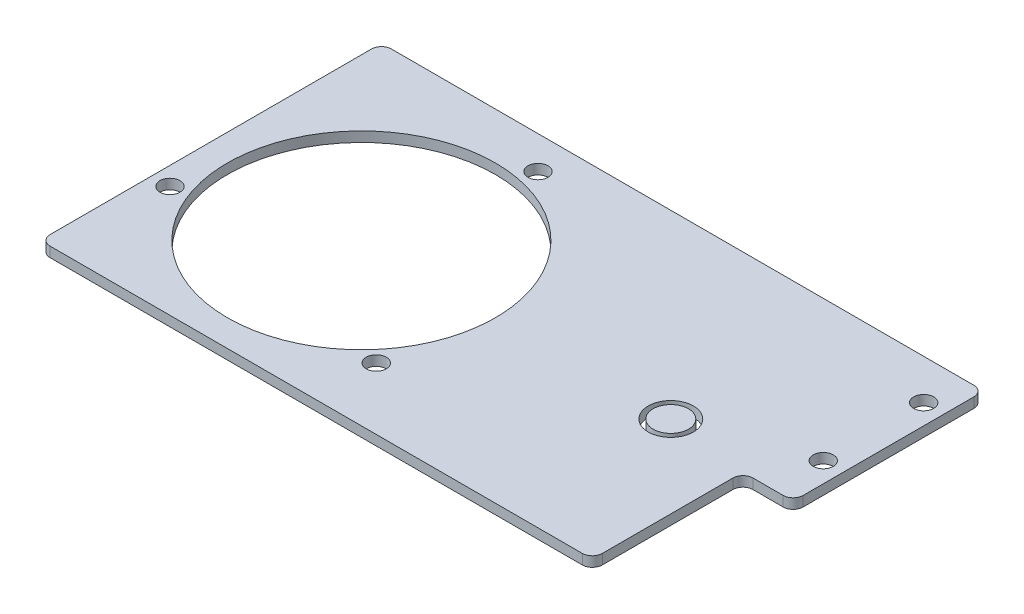
SolidWorks part; units mm, degrees
ref_plane "Front Plane" through (0, 0, 0) normal (0, 0, 1) x (1, 0, 0)
ref_plane "Top Plane" through (0, 0, 0) normal (0, 1, 0) x (1, 0, 0)
ref_plane "Right Plane" through (0, 0, 0) normal (1, 0, 0) x (0, 0, -1)
sketch "Sketch1" plane through (0, 0, 0) normal (0, 1, 0) x (1, 0, 0)
  line L0 (0, 114.3) -> (0, -101.6) construction
  line L1 (273.05, 114.3) -> (-95.25, 114.3)
  line L2 (279.4, 107.95) -> (279.4, 0)
  line L3 (241.3, -101.6) -> (-95.25, -101.6)
  line L4 (-101.6, 107.95) -> (-101.6, -95.25)
  line L5 (254, -6.35) -> (273.05, -6.35)
  line L6 (266.7, 0) -> (266.7, 114.3) construction
  line L7 (-101.6, 0) -> (285.75, 0) construction
  line L8 (0, 0) -> (-101.6, -34.9837) construction
  line L11 (247.65, -95.25) -> (247.65, -12.7)
  circle A0 centre (0, 0) radius 84.7725
  circle A1 centre (0, 0) radius 95.25 construction
  circle A2 centre (-90.0606, -31.0104) radius 6.35
  arc A3 (247.65, -12.7) -> (254, -6.35) centre (254, -12.7) cw
  arc A4 (-95.25, 114.3) -> (-101.6, 107.95) centre (-95.25, 107.95) ccw
  circle A5 centre (18.1746, 93.5) radius 6.35
  circle A6 centre (71.8861, -62.4896) radius 6.35
  arc A7 (-95.25, -101.6) -> (-101.6, -95.25) centre (-95.25, -95.25) cw
  arc A8 (241.3, -101.6) -> (247.65, -95.25) centre (241.3, -95.25) ccw
  arc A9 (273.05, -6.35) -> (279.4, 0) centre (273.05, 0) ccw
  arc A10 (273.05, 114.3) -> (279.4, 107.95) centre (273.05, 107.95) cw
  circle A11 centre (266.7, 88.9) radius 6.35
  circle A12 centre (266.7, 25.4) radius 6.35
  point P0 (0, 0)
  point P11 (0, 0)
  point P21 (247.65, -6.35)
  point P32 (247.65, -101.6)
  point P46 (0, 0)
  dimension "D3" = 169.545
  dimension "D5" = 190.5
  dimension "D6" = 12.7
  dimension "D7" = 114.3
  dimension "D8" = 279.4
  dimension "D11" = 6.35
  dimension "D14" = 12.7
  dimension "D1" = 101.6
  dimension "D2" = 101.6
  dimension "D4" = 19
  dimension "D9" = 95.25
  dimension "D10" = 31.75
  dimension "D13" = 12.7
  dimension "D15" = 25.4
extrude "Boss-Extrude1" add sketch "Sketch1" along normal blind 6.35
sketch "Sketch2" plane through (0, 0, 0) normal (0, -1, 0) x (1, 0, 0)
  line L0 (-101.6, -107.95) -> (-101.6, 95.25) construction
  line L1 (273.05, -114.3) -> (-95.25, -114.3) construction
  line L2 (279.4, 0) -> (279.4, -107.95) construction
  line L3 (-95.25, 101.6) -> (241.3, 101.6) construction
  line L4 (-101.6, -107.95) -> (-101.6, 95.25)
  line L5 (273.05, -114.3) -> (-95.25, -114.3)
  line L6 (279.4, 0) -> (279.4, -107.95)
  line L7 (-95.25, 101.6) -> (241.3, 101.6)
  line L8 (88.9, -114.3) -> (88.9, 101.6) construction
  line L9 (-101.6, -6.35) -> (279.4, -6.35) construction
  line L11 (333.375, 146.05) -> (-155.575, 146.05)
  line L12 (333.375, 146.05) -> (333.375, -158.75)
  line L13 (333.375, -158.75) -> (-155.575, -158.75)
  line L14 (-155.575, 146.05) -> (-155.575, -158.75)
  line L15 (333.375, 146.05) -> (-155.575, -158.75) construction
  line L16 (333.375, -158.75) -> (-155.575, 146.05) construction
  point P12 (88.9, -6.35)
  dimension "D1" = 381
  dimension "D2" = 215.9
  dimension "D3" = 488.95
  dimension "D4" = 304.8
sketch "Sketch3" plane through (0, 6.35, 0) normal (0, 1, 0) x (1, 0, 0)
  circle A0 centre (0, 0) radius 84.7725 construction
  point P0 (84.7725, 0)
sketch "Sketch4" plane through (0, 6.35, 0) normal (0, 1, 0) x (1, 0, 0)
  circle A1 centre (195.6867, 0) radius 11.176 construction
  circle A2 centre (195.6867, 0) radius 14.2875
  circle A3 centre (195.6867, 0) radius 11.176 construction
  circle A4 centre (195.6867, 0) radius 11.176
  dimension "D1" = 28.575
extrude "Cut-Extrude1" cut sketch "Sketch4" against normal blind 9.652
